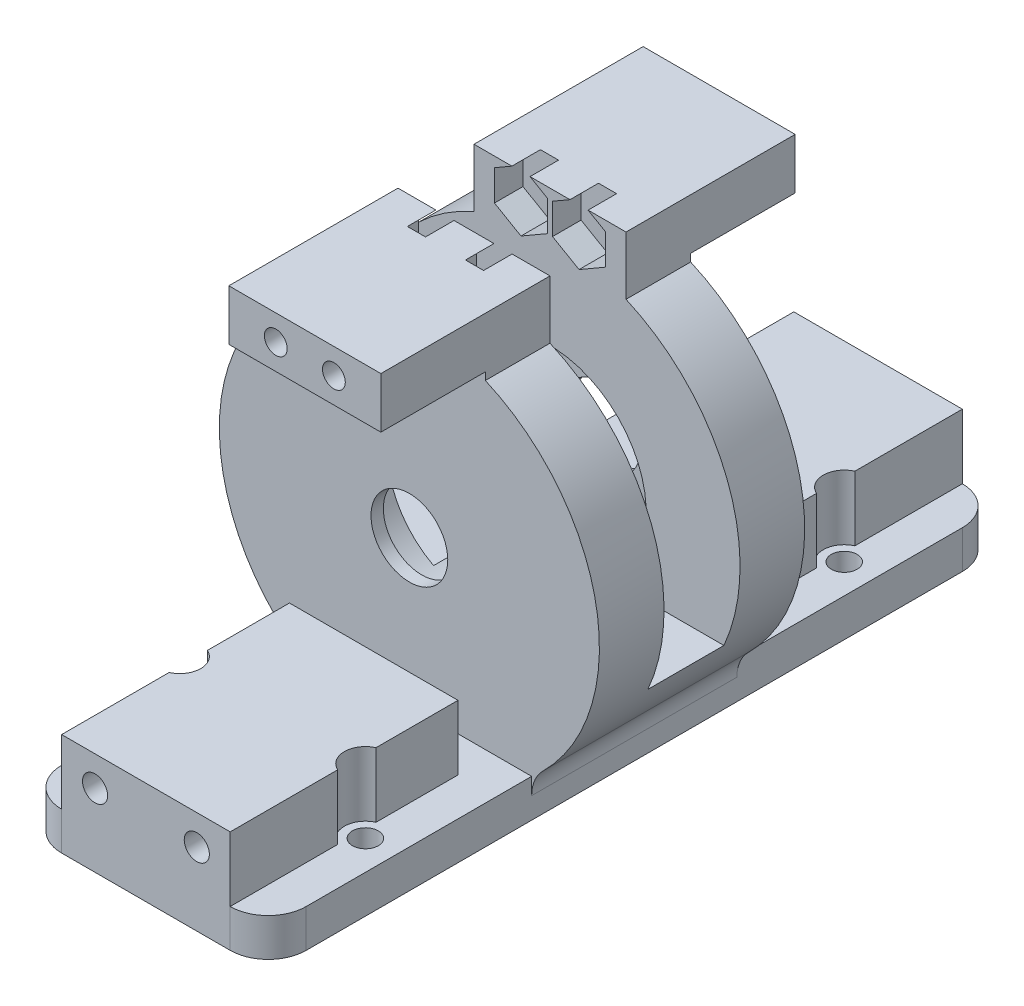
SolidWorks part; units mm, degrees
material "ABS"
ref_plane "Front Plane" through (0, 0, 0) normal (0, 0, 1) x (1, 0, 0)
ref_plane "Top Plane" through (0, 0, 0) normal (0, 1, 0) x (1, 0, 0)
ref_plane "Right Plane" through (0, 0, 0) normal (1, 0, 0) x (0, 0, -1)
sketch "Sketch1" plane through (0, 0, 0) normal (0, 0, 1) x (1, 0, 0)
  line L0 (10.625, 0.4) -> (47, 0.4)
  line L1 (47, 0.4) -> (47, 6.75)
  line L2 (47, 6.75) -> (12.7, 6.75)
  line L5 (0, 31.0549) -> (0, 68.3049) construction
  line L6 (-12.7, 6.75) -> (-47, 6.75)
  line L7 (-47, 6.75) -> (-47, 0.4)
  line L8 (-47, 0.4) -> (-10.625, 0.4)
  line L9 (11.7156, 0) -> (51.6651, 0) construction
  line L10 (0, 13.8049) -> (11.705, 13.8049) construction
  line L11 (-12.7, 69.8924) -> (12.7, 69.8924)
  line L12 (12.7, 6.75) -> (12.7, 69.8924)
  line L13 (-12.7, 6.75) -> (-12.7, 69.8924)
  line L14 (-10.625, 0.4) -> (10.625, 0.4)
  circle A3 centre (0, 31.0549) radius 6.4135
  arc A5 (-12.7, 60.1543) -> (-20.4288, 6.75) centre (0, 31.0549) ccw
  arc A6 (12.7, 60.1543) -> (20.4288, 6.75) centre (0, 31.0549) cw
  point P0 (0, 0.4)
  dimension "D2" = 69.4924
  dimension "D3" = 0.4
  dimension "D6" = 12.827
  dimension "D12" = 31.75
  dimension "D4" = 1.5875
  dimension "D5" = 17.25
  dimension "D7" = 6.35
  dimension "D8" = 36.375
  dimension "D9" = 37.25
  dimension "D10" = 25.4
  dimension "D11" = 21.25
extrude "Boss-Extrude1" add sketch "Sketch1" along normal blind 34.29
sketch "Sketch3" plane through (12.7, 0, 0) normal (1, 0, 0) x (0, 0, -1)
  line L1 (-23.495, 18.2499) -> (-10.795, 18.2499)
  line L4 (-10.795, 18.2499) -> (-10.795, 69.8924)
  line L5 (-23.495, 18.2499) -> (-10.795, 69.8924) construction
  line L6 (-23.495, 69.8924) -> (-10.795, 18.2499) construction
  line L9 (-34.29, 69.8924) -> (0, 69.8924) construction
  line L13 (-23.495, 69.8924) -> (-10.795, 69.8924)
  line L14 (-34.29, 69.8924) -> (0, 69.8924) construction
  line L15 (-23.495, 69.8924) -> (-23.495, 18.2499)
  point P4 (-17.145, 44.0711)
  point P9 (-17.145, 69.8924)
  point P14 (-17.145, 69.8924)
  dimension "D1" = 12.7
  dimension "D2" = 51.6425
extrude "Cut-Extrude1" cut sketch "Sketch3" against normal up to next and the other way up to next
sketch "Sketch5" plane through (0, 6.75, 0) normal (0, 1, 0) x (1, 0, 0)
  line L1 (-40, -6.35) -> (40, -6.35) construction
  line L2 (-40, -6.35) -> (-40, -27.94) construction
  line L3 (-40, -27.94) -> (40, -27.94) construction
  line L4 (40, -6.35) -> (40, -27.94) construction
  line L5 (-40, -6.35) -> (40, -27.94) construction
  line L6 (-40, -27.94) -> (40, -6.35) construction
  line L10 (47, -34.29) -> (20.4288, -34.29) construction
  line L11 (47, 0) -> (20.4288, 0) construction
  circle A0 centre (40, -27.94) radius 2.159
  circle A1 centre (40, -6.35) radius 2.159
  circle A2 centre (-40, -6.35) radius 2.159
  circle A3 centre (-40, -27.94) radius 2.159
  point P11 (0, -17.145)
  dimension "D1" = 4.318
  dimension "D2" = 6.35
  dimension "D3" = 6.35
  dimension "D4" = 40
extrude "Cut-Extrude2" cut sketch "Sketch5" against normal through all
sketch "Sketch6" plane through (0, 0, 34.29) normal (0, 0, 1) x (1, 0, 0)
  line L0 (0, 31.0549) -> (0, 68.3049) construction
  line L1 (-4.8514, 65.6525) -> (4.8514, 65.6525) construction
  line L2 (-12.7, 69.8924) -> (12.7, 69.8924)
  line L4 (-12.7, 61.4126) -> (12.7, 61.4126)
  line L5 (0, 65.6525) -> (0, 16.6305) construction
  line L6 (-6.6075, 41.1415) -> (10.2894, 41.1415) construction
  line L11 (12.7, 61.4126) -> (12.7, 69.8924)
  line L12 (-12.7, 61.4126) -> (-12.7, 69.8924)
  line L15 (-12.7, 69.8924) -> (12.7, 69.8924) construction
  line L16 (12.7, 60.1543) -> (12.7, 69.8924) construction
  circle A1 centre (0, 31.0549) radius 6.4135 construction
  circle A2 centre (4.8514, 65.6525) radius 1.5494 construction
  circle A3 centre (-4.8514, 65.6525) radius 1.5494 construction
  circle A4 centre (4.8514, 65.6525) radius 2 construction
  circle A11 centre (0, 31.0549) radius 6.4135 construction
  point P7 (0, 65.6525)
  point P23 (0, 41.1415)
  dimension "D4" = 3.0988
  dimension "D5" = 4
  dimension "D1" = 37.25
  dimension "D2" = 9.7028
  dimension "D3" = 2.6524
extrude "Boss-Extrude2" add sketch "Sketch6" along normal blind 17.4625
sketch "Sketch8" plane through (0, 0, 51.7525) normal (0, 0, 1) x (1, 0, 0)
  line L0 (-29.2283, 41.1415) -> (25.3756, 41.1415) construction
  line L1 (0, 41.1415) -> (0, 61.4126) construction
  line L2 (-12.7, 61.4126) -> (12.7, 61.4126) construction
  line L5 (0, 69.8924) -> (0, 65.6525) construction
  line L7 (-4.8514, 65.6525) -> (4.8514, 65.6525) construction
  line L8 (-12.7, 61.4126) -> (12.7, 61.4126) construction
  line L9 (12.7, 69.8924) -> (-12.7, 69.8924) construction
  circle A0 centre (-4.8514, 65.6525) radius 1.905
  circle A1 centre (4.8514, 65.6525) radius 1.905
  dimension "D1" = 3.81
  dimension "D2" = 9.7028
sketch "Sketch12" plane through (0, 0, 23.495) normal (0, 0, 1) x (1, 0, 0)
  circle A0 centre (0, 31.0549) radius 14.478
  dimension "D1" = 28.956
extrude "Cut-Extrude9" cut sketch "Sketch12" along normal blind 8.7312 and the other way blind 6.35
ref_plane "Plane1" through (0, 0, 17.145) normal (0, 0, -1) x (-1, 0, 0)
extrude "Cut-Extrude11" cut sketch "Sketch8" against normal up to surface (40.9575 mm away)
sketch "Sketch14" plane through (0, 0, 23.495) normal (0, 0, -1) x (-1, 0, 0)
  line L0 (12.7, 69.8924) -> (-12.7, 69.8924) construction
  line L1 (-0.4223, 63.0953) -> (-0.4223, 68.2097)
  line L2 (-0.4223, 68.2097) -> (-4.8514, 70.7668)
  line L3 (-4.8514, 70.7668) -> (-9.2805, 68.2097)
  line L4 (-9.2805, 68.2097) -> (-9.2805, 63.0953)
  line L5 (-9.2805, 63.0953) -> (-4.8514, 60.5382)
  line L6 (-4.8514, 60.5382) -> (-0.4223, 63.0953)
  line L7 (9.2805, 63.0953) -> (9.2805, 68.2097)
  line L8 (9.2805, 68.2097) -> (4.8514, 70.7668)
  line L9 (4.8514, 70.7668) -> (0.4223, 68.2097)
  line L10 (0.4223, 68.2097) -> (0.4223, 63.0953)
  line L11 (0.4223, 63.0953) -> (4.8514, 60.5382)
  line L12 (4.8514, 60.5382) -> (9.2805, 63.0953)
  line L13 (6.3659, 69.8924) -> (-6.3659, 69.8924)
  circle A0 centre (-4.8514, 65.6525) radius 4.4291 construction
  circle A1 centre (4.8514, 65.6525) radius 4.4291 construction
  circle M13 centre (-4.8514, 65.6525) radius 1.905
  circle M14 centre (4.8514, 65.6525) radius 1.905
  line M19 (12.7, 69.8924) -> (-12.7, 69.8924)
  dimension "D1" = 8.8582
extrude "Cut-Extrude12" cut sketch "Sketch14" against normal blind 4.7625 contours L5 L6 L1 L2 L3 L4 M19 M13 | L11 L12 L7 L8 L9 L10 M19 M14
mirror "Mirror4" about plane through (0, 0, 17.145) normal (0, 0, -1) of "Cut-Extrude9", "Cut-Extrude12", "Cut-Extrude11", "Boss-Extrude2"
fillet "Fillet4" radius 6.35 4 edges at (-47, 3.575, 0) (-47, 3.575, 34.29) (47, 3.575, 0) (47, 3.575, 34.29)
chamfer "Chamfer1" distance 1.5875 angle 45 1 edges at (0, 45.5329, 10.795)
sketch "Sketch15" plane through (0, 6.75, 0) normal (0, 1, 0) x (1, 0, 0)
  line L0 (20.4288, 1.0134) -> (20.4288, -35.3034)
  line L1 (25.4, -34.29) -> (40.65, -34.29)
  line L2 (47, -27.94) -> (47, -6.35)
  line L3 (40.65, 0) -> (25.4, 0)
  line L4 (40.65, 0) -> (20.4288, 0) construction
  line L6 (0, -55) -> (0, 55) construction
  line L7 (-40.65, 0) -> (-25.4, 0)
  line L8 (-47, -27.94) -> (-47, -6.35)
  line L9 (-25.4, -34.29) -> (-40.65, -34.29)
  line L10 (-20.4288, 1.0134) -> (-20.4288, -35.3034)
  arc A1 (40.65, -34.29) -> (47, -27.94) centre (40.65, -27.94) ccw
  arc A2 (47, -6.35) -> (40.65, 0) centre (40.65, -6.35) ccw
  arc A3 (20.4288, 1.0134) -> (25.4, 0) centre (25.4, 12.7) ccw construction
  arc A4 (25.4, 0) -> (20.4288, 1.0134) centre (25.4, 12.7) cw
  arc A5 (20.4288, -35.3034) -> (25.4, -34.29) centre (25.4, -46.99) cw
  arc A6 (-20.4288, -35.3034) -> (-25.4, -34.29) centre (-25.4, -46.99) ccw
  arc A7 (-25.4, 0) -> (-20.4288, 1.0134) centre (-25.4, 12.7) ccw
  arc A8 (-47, -6.35) -> (-40.65, 0) centre (-40.65, -6.35) cw
  arc A9 (-40.65, -34.29) -> (-47, -27.94) centre (-40.65, -27.94) cw
extrude "Cut-Extrude13" cut sketch "Sketch15" against normal through all
ref_plane "Plane2" through (0, 0, 17.145) normal (0, 0, -1) x (-1, 0, 0)
sketch "Sketch16" plane through (0, 0, 17.145) normal (0, 0, -1) x (-1, 0, 0)
  line L0 (-20.4288, 4.7082) -> (-20.4288, 0.4) construction
  line L1 (-20.4288, 6.75) -> (20.4288, 6.75)
  line L2 (-20.4288, 6.75) -> (-20.4288, 0.4)
  line L3 (-20.4288, 0.4) -> (20.4288, 0.4)
  line L4 (20.4288, 6.75) -> (20.4288, 0.4)
  line L5 (-20.4288, 6.75) -> (20.4288, 0.4) construction
  line L6 (-20.4288, 0.4) -> (20.4288, 6.75) construction
  point P0 (0, 3.575)
extrude "Boss-Extrude3" add sketch "Sketch16" along normal mid plane 122.32
sketch "Sketch17" plane through (0, 0.4, 0) normal (0, -1, 0) x (1, 0, 0)
  line L0 (-28.4034, 17.145) -> (28.4034, 17.145) construction
  line L1 (-15.5, -22.855) -> (15.5, -22.855) construction
  line L2 (-15.5, -22.855) -> (-15.5, 57.145) construction
  line L3 (-15.5, 57.145) -> (15.5, 57.145) construction
  line L4 (15.5, -22.855) -> (15.5, 57.145) construction
  line L5 (-15.5, -22.855) -> (15.5, 57.145) construction
  line L6 (-15.5, 57.145) -> (15.5, -22.855) construction
  circle A0 centre (15.5, 57.145) radius 2.159
  circle A1 centre (-15.5, 57.145) radius 2.159
  circle A2 centre (15.5, -22.855) radius 2.159
  circle A3 centre (-15.5, -22.855) radius 2.159
  point P0 (0, 17.145)
  dimension "D3" = 4.318
  dimension "D1" = 80
  dimension "D2" = 31
extrude "Cut-Extrude14" cut sketch "Sketch17" against normal up to surface (6.35 mm away) up to face at (0, 6.75, 56.2975)
fillet "Fillet5" radius 6.35 6 edges at (-20.4288, 6.75, 17.145) (20.4288, 6.75, 17.145) (-20.4288, 3.575, -44.015) (20.4288, 3.575, -44.015) (-20.4288, 3.575, 78.305) (20.4288, 3.575, 78.305)
sketch "Sketch18" plane through (0, 6.75, 0) normal (0, 1, 0) x (1, 0, 0)
  line L1 (-14.0788, -78.305) -> (14.0788, -78.305)
  line L2 (-14.0788, -78.305) -> (-14.0788, -40.245)
  line L3 (-14.0788, -40.245) -> (14.0788, -40.245)
  line L4 (14.0788, -78.305) -> (14.0788, -40.245)
  dimension "D1" = 38.06
extrude "Boss-Extrude4" add sketch "Sketch18" along normal blind 10.8
mirror "Mirror5" about plane through (0, 0, 17.145) normal (0, 0, -1) of "Boss-Extrude4"
sketch "Sketch19" plane through (0, 0, -44.015) normal (0, 0, -1) x (-1, 0, 0)
  line L0 (-8.5, 17.55) -> (8.5, 17.55)
  line L1 (14.0788, 17.55) -> (-14.0788, 17.55) construction
  line L2 (8.5, 17.55) -> (8.5, 12.5549)
  line L3 (0, 17.55) -> (0, 15.1447)
  circle A0 centre (8.5, 12.5549) radius 2.1
  circle A1 centre (-8.5, 12.5549) radius 2.1
  point P5 (0, 17.55)
  dimension "D2" = 4.2
  dimension "D1" = 4.9951
extrude "Cut-Extrude15" cut sketch "Sketch19" against normal blind 40
mirror "Mirror6" about plane through (0, 0, 17.145) normal (0, 0, -1) of "Cut-Extrude15"
sketch "Sketch21" plane through (0, 6.75, 0) normal (0, 1, 0) x (1, 0, 0)
  circle A0 centre (15.5, -57.145) radius 3.5
  dimension "D1" = 7
extrude "Cut-Extrude16" cut sketch "Sketch21" along normal blind 11
sketch "Sketch22" plane through (0, 6.75, 0) normal (0, 1, 0) x (1, 0, 0)
  circle A0 centre (-15.5, -57.145) radius 3.5
  dimension "D1" = 7
extrude "Cut-Extrude17" cut sketch "Sketch22" along normal blind 11
mirror "Mirror7" about plane through (0, 0, 17.145) normal (0, 0, -1) of "Cut-Extrude16", "Cut-Extrude17"
equation "\"D3@Sketch5\"=\"D2@Sketch5\""
